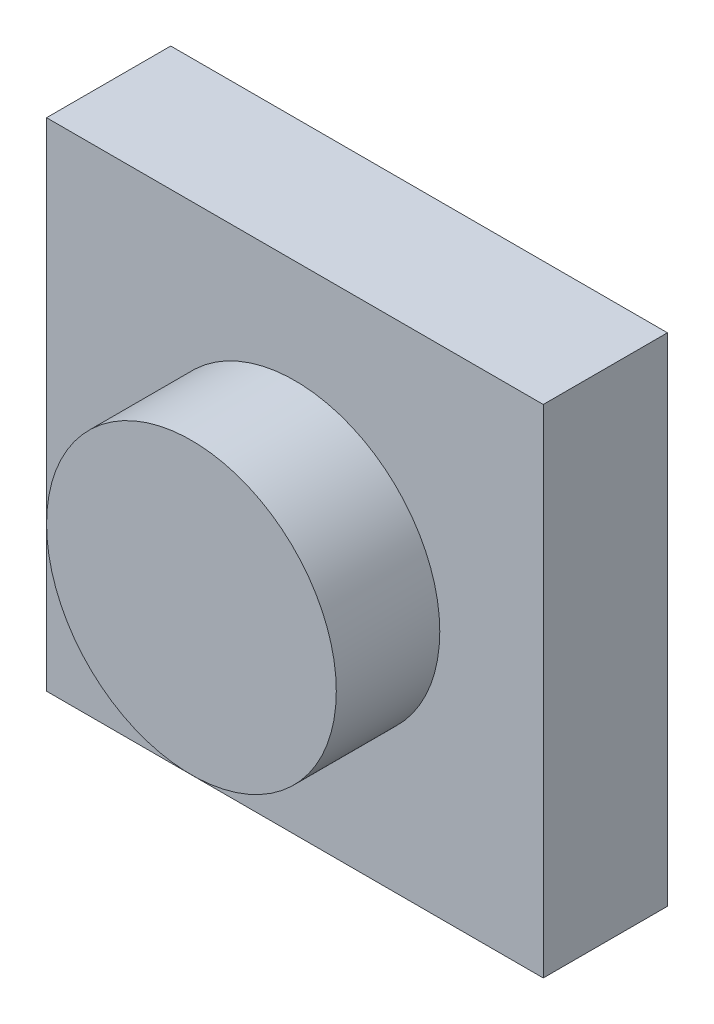
SolidWorks part; units mm, degrees
ref_plane "Front Plane" through (0, 0, 0) normal (0, 0, 1) x (1, 0, 0)
ref_plane "Top Plane" through (0, 0, 0) normal (0, 1, 0) x (1, 0, 0)
ref_plane "Right Plane" through (0, 0, 0) normal (1, 0, 0) x (0, 0, -1)
other "Configuration Table"
sketch "Sketch1" plane through (0, 0, 0) normal (0, 0, 1) x (1, 0, 0)
  line L1 (0, 0) -> (120, 0)
  line L2 (0, 0) -> (0, 120)
  line L3 (0, 120) -> (120, 120)
  line L4 (120, 0) -> (120, 120)
  dimension "D1" = 120
  dimension "D2" = 120
extrude "Boss-Extrude1" add sketch "Sketch1" along normal blind 30
sketch "Sketch2" plane through (0, 0, 30) normal (0, 0, 1) x (1, 0, 0)
  line L0 (120, 120) -> (0, 120) construction
  line L1 (120, 0) -> (120, 120) construction
  circle A0 centre (60, 60) radius 35
  dimension "D1" = 70
  dimension "D2" = 60
  dimension "D3" = 60
extrude "Boss-Extrude2" add sketch "Sketch2" along normal blind 25
